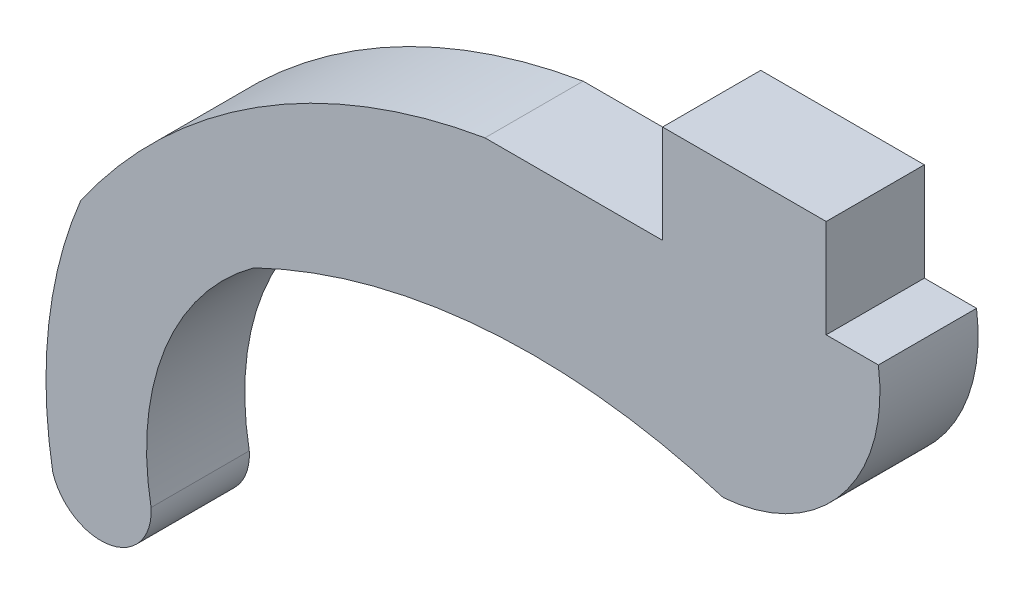
SolidWorks part; units mm, degrees
ref_plane "Front Plane" through (0, 0, 0) normal (0, 0, 1) x (1, 0, 0)
ref_plane "Top Plane" through (0, 0, 0) normal (0, 1, 0) x (1, 0, 0)
ref_plane "Right Plane" through (0, 0, 0) normal (1, 0, 0) x (0, 0, -1)
sketch "Sketch1" plane through (0, 0, 0) normal (0, 0, 1) x (1, 0, 0)
  line L0 (-111.8457, 0) -> (-111.8457, -1.524)
  line L1 (-111.8457, 0) -> (-109.3057, 0)
  line L2 (-109.3057, 0) -> (-109.3057, -1.524)
  line L3 (-109.3057, -1.524) -> (-108.4956, -1.524)
  line L4 (-111.8457, -1.524) -> (-114.6025, -1.524)
  arc A0 (-108.4956, -1.524) -> (-110.9055, -4.5109) centre (-111.1059, -1.8836) cw
  arc A1 (-110.9055, -4.5109) -> (-118.1938, -5.0669) centre (-113.8449, -14.0272) ccw
  arc A2 (-118.1938, -5.0669) -> (-119.7852, -9.0849) centre (-115.8069, -8.3365) ccw
  arc A3 (-119.7852, -9.0849) -> (-121.3117, -9.3721) centre (-120.5654, -9.1387) cw
  arc A4 (-114.6025, -1.524) -> (-120.8783, -5.5067) centre (-112.9968, -10.9903) ccw
  arc A5 (-120.8783, -5.5067) -> (-121.3117, -9.3721) centre (-114.5237, -8.1762) ccw
extrude "Boss-Extrude1" add sketch "Sketch1" along normal blind 1.524
